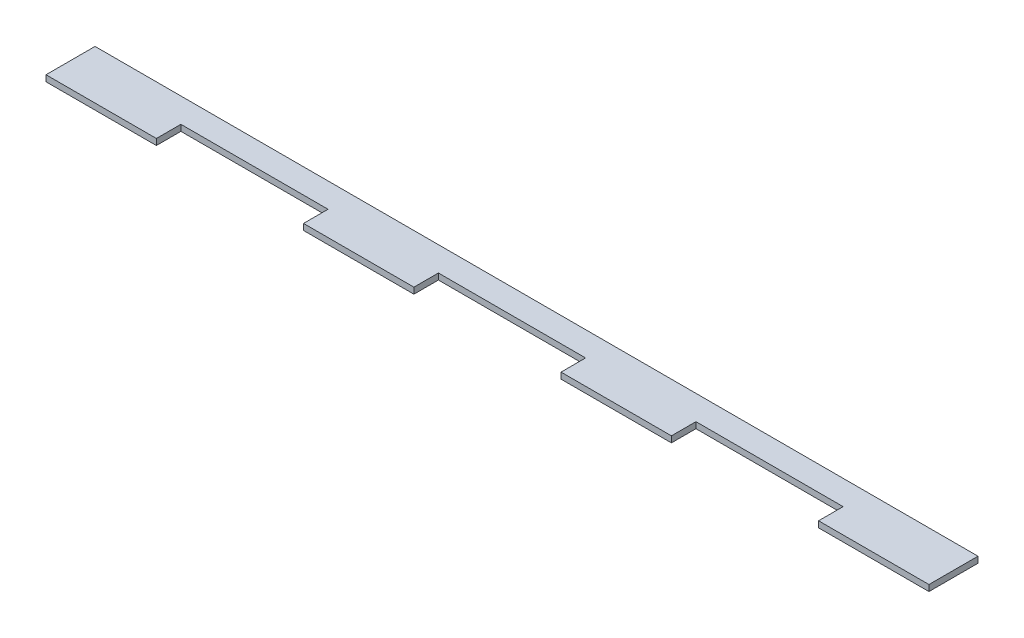
SolidWorks part; units mm, degrees
ref_plane "Front Plane" through (0, 0, 0) normal (0, 0, 1) x (1, 0, 0)
ref_plane "Top Plane" through (0, 0, 0) normal (0, 1, 0) x (1, 0, 0)
ref_plane "Right Plane" through (0, 0, 0) normal (1, 0, 0) x (0, 0, -1)
sketch "Sketch1" plane through (0, 0, 0) normal (0, 1, 0) x (1, 0, 0)
  line L1 (-39.5348, 67.9084) -> (1789.2652, 67.9084)
  line L2 (-39.5348, 67.9084) -> (-39.5348, -33.6916)
  line L3 (-39.5348, -33.6916) -> (1789.2652, -33.6916)
  line L4 (1789.2652, 67.9084) -> (1789.2652, -33.6916)
extrude "Boss-Extrude1" add sketch "Sketch1" along normal blind 12.7
sketch "Sketch2" plane through (0, 12.7, 0) normal (0, 1, 0) x (1, 0, 0)
  line L0 (-39.5348, -33.6916) -> (341.4652, -33.6916) construction
  line L1 (-39.5348, -33.6916) -> (1789.2652, -33.6916) construction
  line L2 (341.4652, -33.6916) -> (189.0652, -33.6916)
  line L3 (189.0652, -33.6916) -> (189.0652, 17.1084)
  line L4 (189.0652, 17.1084) -> (493.8652, 17.1084)
  line L5 (493.8652, 17.1084) -> (493.8652, -33.6916)
  line L6 (493.8652, -33.6916) -> (341.4652, -33.6916)
  line L7 (1789.2652, -33.6916) -> (1408.2652, -33.6916) construction
  line L8 (1408.2652, -33.6916) -> (1255.8652, -33.6916)
  line L9 (1255.8652, -33.6916) -> (1255.8652, 17.1084)
  line L10 (1560.6652, 17.1084) -> (1560.6652, -33.6916)
  line L11 (1560.6652, -33.6916) -> (1408.2652, -33.6916)
  line L12 (1255.8652, 17.1084) -> (1560.6652, 17.1084)
  line L13 (-39.5348, -33.6916) -> (874.8652, -33.6916) construction
  line L14 (874.8652, -33.6916) -> (722.4652, -33.6916)
  line L15 (722.4652, -33.6916) -> (722.4652, 17.1084)
  line L16 (1027.2652, 17.1084) -> (1027.2652, -33.6916)
  line L17 (1027.2652, -33.6916) -> (874.8652, -33.6916)
  line L18 (722.4652, 17.1084) -> (1027.2652, 17.1084)
  dimension "D1" = 152.4
  dimension "D2" = 152.4
  dimension "D3" = 381
  dimension "D4" = 914.4
  dimension "D5" = 152.4
  dimension "D6" = 152.4
  dimension "D7" = 381
extrude "Cut-Extrude1" cut sketch "Sketch2" against normal blind 12.7
